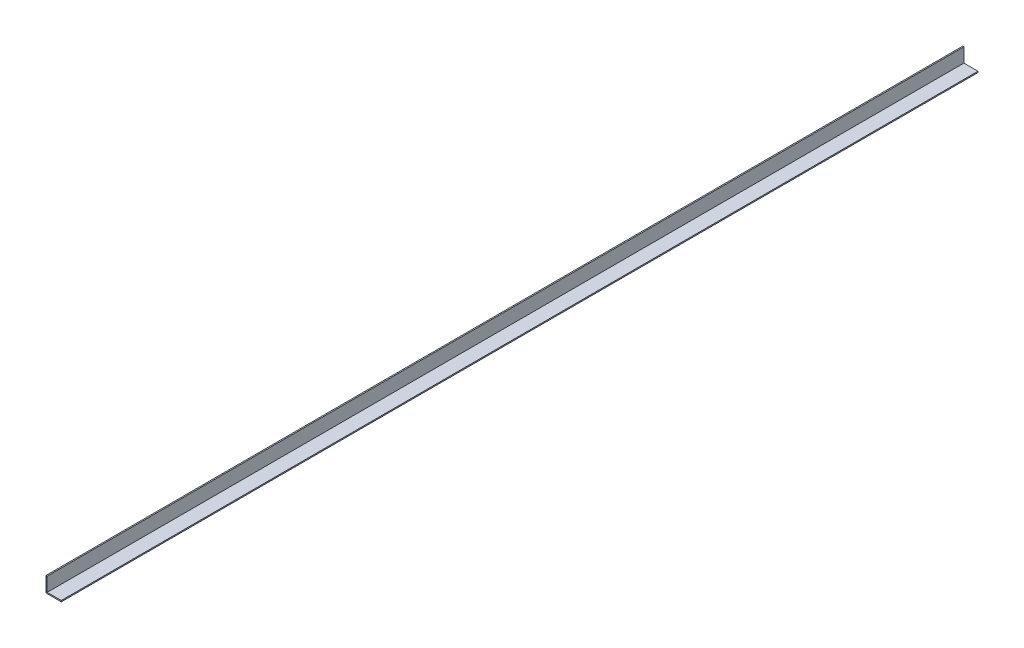
SolidWorks part; units mm, degrees
material "ASTM A36 Acero"
ref_plane "Alzado" through (0, 0, 0) normal (0, 0, 1) x (1, 0, 0)
ref_plane "Planta" through (0, 0, 0) normal (0, 1, 0) x (1, 0, 0)
ref_plane "Vista lateral" through (0, 0, 0) normal (1, 0, 0) x (0, 0, -1)
sketch "Croquis1" plane through (0, 0, 0) normal (0, 0, 1) x (1, 0, 0)
  line L0 (0, 101.6) -> (0, 0)
  line L1 (0, 0) -> (101.6, 0)
  line L2 (101.6, 0) -> (101.6, 7.94)
  line L3 (101.6, 7.94) -> (7.94, 7.94)
  line L4 (7.94, 7.94) -> (7.94, 101.6)
  line L5 (7.94, 101.6) -> (0, 101.6)
  dimension "D1" = 7.94
  dimension "D2" = 101.6
extrude "Saliente-Extruir1" add sketch "Croquis1" against normal blind 6100
